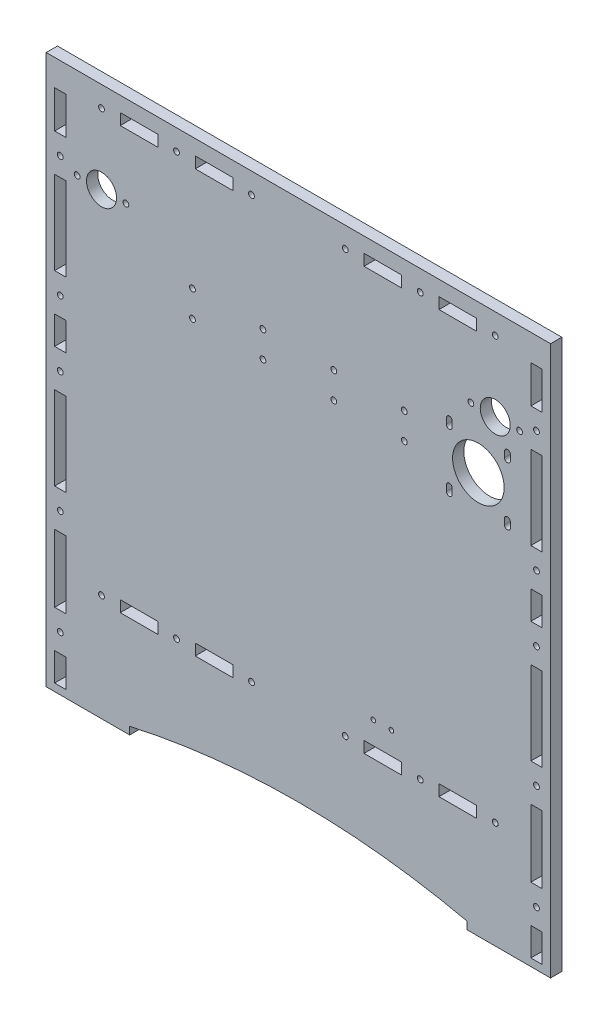
SolidWorks part; units mm, degrees
ref_plane "Front Plane" through (0, 0, 0) normal (0, 0, 1) x (1, 0, 0)
ref_plane "Top Plane" through (0, 0, 0) normal (0, 1, 0) x (1, 0, 0)
ref_plane "Right Plane" through (0, 0, 0) normal (1, 0, 0) x (0, 0, -1)
sketch "Sketch1" plane through (0, 0, 0) normal (0, 0, 1) x (1, 0, 0)
  line L1 (0, 0) -> (260, 0)
  line L2 (0, 0) -> (0, 270)
  line L3 (0, 270) -> (260, 270)
  line L4 (260, 0) -> (260, 270)
  dimension "D1" = 270
  dimension "D2" = 260
extrude "Boss-Extrude1" add sketch "Sketch1" along normal blind 6
sketch "Sketch2" plane through (0, 0, 0) normal (0, 0, -1) x (-1, 0, 0)
  line L0 (-130, 270) -> (-130, 0) construction
  line L1 (-225, 56) -> (-205, 56)
  line L2 (-225, 56) -> (-225, 50)
  line L3 (-225, 50) -> (-205, 50)
  line L4 (-205, 56) -> (-205, 50)
  line L5 (-185, 56) -> (-165, 56)
  line L6 (-185, 56) -> (-185, 50)
  line L7 (-185, 50) -> (-165, 50)
  line L8 (-165, 56) -> (-165, 50)
  line L9 (-260, 270) -> (0, 270) construction
  line L10 (0, 0) -> (-260, 0) construction
  line L11 (-260, 0) -> (-260, 270) construction
  line L12 (-225, 53) -> (-165, 53) construction
  line L13 (-130, 0) -> (-130, -73.8705) construction
  line L14 (-130, -73.8705) -> (-130, -196.098) construction
  line L16 (-220, 0) -> (-40, 0)
  line L17 (-75, 50) -> (-95, 50)
  line L18 (-95, 56) -> (-95, 50)
  line L19 (-75, 56) -> (-95, 56)
  line L20 (-75, 56) -> (-75, 50)
  line L21 (-35, 50) -> (-55, 50)
  line L22 (-55, 56) -> (-55, 50)
  line L23 (-35, 56) -> (-55, 56)
  line L24 (-35, 56) -> (-35, 50)
  arc A0 (-220, 0) -> (-40, 0) centre (-130, -400) cw
  point P23 (-130, 10)
  point P26 (-130, 10)
  dimension "D9" = 40
  dimension "D1" = 35
  dimension "D2" = 20
  dimension "D3" = 20
  dimension "D4" = 20
  dimension "D5" = 6
  dimension "D6" = 6
  dimension "D7" = 50
  dimension "D8" = 3
  dimension "D12" = 10
extrude "Cut-Extrude1" cut sketch "Sketch2" against normal blind 6
sketch "Sketch4" plane through (0, 0, 0) normal (0, 0, -1) x (-1, 0, 0)
  line L1 (-260, 270) -> (-254, 270)
  line L2 (-260, 270) -> (-260, 264)
  line L5 (-220, 0) -> (-260, 0) construction
  line L6 (-260, 270) -> (-254, 270)
  line L7 (-260, 270) -> (-260, 255)
  line L8 (-260, 0) -> (-254, 0)
  line L9 (-254, 264) -> (-254, 255)
  line L11 (-254, 15) -> (-260, 15)
  line L13 (-254, 35) -> (-260, 35)
  line L15 (-254, 71) -> (-260, 71)
  line L17 (-254, 91) -> (-260, 91)
  line L19 (-260, 135.5) -> (-254, 135.5)
  line L21 (-260, 155.5) -> (-254, 155.5)
  line L23 (-254, 170.5) -> (-260, 170.5)
  line L25 (-254, 190.5) -> (-260, 190.5)
  line L27 (-254, 235) -> (-260, 235)
  line L29 (-254, 255) -> (-260, 255)
  line L33 (-254, 264) -> (-254, 270)
  line L36 (-205, 56) -> (-225, 56) construction
  line L38 (-130, 270) -> (-130, 0) construction
  line L39 (-260, 270) -> (0, 270) construction
  line L40 (-260, 15) -> (-260, 0)
  line L41 (-260, 270) -> (-254, 270)
  line L42 (-260, 270) -> (-260, 255)
  line L43 (-260, 255) -> (-254, 255)
  line L44 (-254, 270) -> (-254, 255)
  line L45 (-260, 235) -> (-254, 235)
  line L46 (-260, 235) -> (-260, 190.5)
  line L47 (-260, 190.5) -> (-254, 190.5)
  line L48 (-254, 235) -> (-254, 190.5)
  line L49 (-260, 170.5) -> (-254, 170.5)
  line L50 (-260, 170.5) -> (-260, 155.5)
  line L51 (-260, 155.5) -> (-254, 155.5)
  line L52 (-254, 170.5) -> (-254, 155.5)
  line L53 (-260, 135.5) -> (-254, 135.5)
  line L54 (-260, 135.5) -> (-260, 91)
  line L55 (-260, 91) -> (-254, 91)
  line L56 (-254, 135.5) -> (-254, 91)
  line L57 (-260, 71) -> (-254, 71)
  line L58 (-260, 71) -> (-260, 35)
  line L59 (-260, 35) -> (-254, 35)
  line L60 (-254, 71) -> (-254, 35)
  line L61 (-260, 15) -> (-254, 15)
  line L62 (-260, 15) -> (-260, 0)
  line L63 (-260, 0) -> (-254, 0)
  line L64 (-254, 15) -> (-254, 0)
  line L65 (-254, 71) -> (-254, 35)
  line L66 (-260, 71) -> (-260, 35)
  line L67 (-254, 135.5) -> (-254, 91)
  line L68 (-260, 135.5) -> (-260, 91)
  line L69 (-254, 170.5) -> (-254, 155.5)
  line L70 (-260, 170.5) -> (-260, 155.5)
  line L71 (-254, 235) -> (-254, 190.5)
  line L72 (-260, 235) -> (-260, 190.5)
  line L73 (-254, 15) -> (-254, 0)
  line L74 (0, 0) -> (-6, 0)
  line L75 (-6, 15) -> (-6, 0)
  line L76 (0, 15) -> (-6, 15)
  line L77 (0, 15) -> (0, 0)
  line L78 (0, 35) -> (-6, 35)
  line L79 (-6, 71) -> (-6, 35)
  line L80 (0, 71) -> (-6, 71)
  line L81 (0, 71) -> (0, 35)
  line L82 (0, 91) -> (-6, 91)
  line L83 (-6, 135.5) -> (-6, 91)
  line L84 (0, 135.5) -> (-6, 135.5)
  line L85 (0, 135.5) -> (0, 91)
  line L86 (0, 155.5) -> (-6, 155.5)
  line L87 (-6, 170.5) -> (-6, 155.5)
  line L88 (0, 170.5) -> (-6, 170.5)
  line L89 (0, 170.5) -> (0, 155.5)
  line L90 (0, 190.5) -> (-6, 190.5)
  line L91 (-6, 235) -> (-6, 190.5)
  line L92 (0, 235) -> (-6, 235)
  line L93 (0, 235) -> (0, 190.5)
  line L94 (0, 255) -> (-6, 255)
  line L95 (-6, 270) -> (-6, 255)
  line L96 (0, 270) -> (-6, 270)
  line L97 (0, 270) -> (0, 255)
  point P33 (-257, 170.5)
  point P34 (-257, 71)
  line M60 (-40, 0) -> (0, 0)
  line M61 (0, 0) -> (0, 270)
  line M62 (0, 270) -> (-260, 270)
  line M63 (-260, 270) -> (-260, 0)
  line M64 (-260, 0) -> (-220, 0)
  dimension "D1" = 6
  dimension "D2" = 15
  dimension "D3" = 20
  dimension "D4" = 20
  dimension "D5" = 15
  dimension "D6" = 44.5
  dimension "D7" = 15
  dimension "D8" = 20
  dimension "D10" = 20
  dimension "D11" = 20
  dimension "D12" = 15
extrude "Cut-Extrude3" cut sketch "Sketch4" against normal blind 6 contours L9 L33 L29 M62 M63 | L48 L27 L25 M63 | L52 L23 L21 M63 | L56 L19 L17 M63 | L60 L15 L13 M63 | L64 L11 M63 M64 | L76 L75 M61 M60 | L80 L79 L78 M61 | L84 L83 L82 M61 | L92 L91 L90 M61 | L95 L94 M62 M61 | L89 L86 L87 L88
sketch "Sketch5" plane through (0, 0, 0) normal (0, 0, -1) x (-1, 0, 0)
  line L0 (-130, 270) -> (-130, 190.9639) construction
  line L1 (-254, 270) -> (-6, 270) construction
  line L2 (-260, 235) -> (-260, 255) construction
  circle A0 centre (-235, 240.5) radius 8
  circle A1 centre (-25, 240.5) radius 8
  dimension "D1" = 16
  dimension "D3" = 25
  dimension "D2" = 29.5
extrude "Cut-Extrude4" cut sketch "Sketch5" against normal blind 10
sketch "Sketch6" plane through (0, 0, 0) normal (0, 0, -1) x (-1, 0, 0)
  line L0 (-130, 270) -> (-130, 162.347) construction
  line L1 (-254, 270) -> (-6, 270) construction
  line L2 (-243, 240.5) -> (-227, 240.5) construction
  line L3 (-235, 248.5) -> (-235, 232.5) construction
  line L4 (-248, 240.5) -> (-222, 240.5) construction
  line L5 (-254, 235) -> (-254, 190.5) construction
  circle A0 centre (-235, 240.5) radius 8 construction
  circle A1 centre (-235, 240.5) radius 8
  circle A2 centre (-248, 240.5) radius 1.55
  circle A3 centre (-222, 240.5) radius 1.55
  circle A4 centre (-12, 240.5) radius 1.55
  circle A5 centre (-38, 240.5) radius 1.55
  dimension "D4" = 3.1
  dimension "D3" = 6
extrude "Cut-Extrude5" cut sketch "Sketch6" against normal blind 6
sketch "Sketch7" plane through (0, 0, 0) normal (0, 0, -1) x (-1, 0, 0)
  line L0 (-130, 270) -> (-130, 302.4373) construction
  line L1 (-254, 270) -> (-6, 270) construction
  line L2 (-186.5, 219) -> (-186.5, 205) construction
  line L4 (-189.7779, 212) -> (-134.7801, 212) construction
  circle A0 centre (-186.5, 205) radius 1.55
  circle A1 centre (-148.9, 205) radius 1.55
  circle A2 centre (-148.9, 219) radius 1.55
  circle A3 centre (-186.5, 219) radius 1.55
  circle A4 centre (-73.5, 205) radius 1.55
  circle A5 centre (-111.1, 205) radius 1.55
  circle A6 centre (-111.1, 219) radius 1.55
  circle A7 centre (-73.5, 219) radius 1.55
  dimension "D1" = 3.1
  dimension "D4" = 7
  dimension "D5" = 37.6
  dimension "D6" = 14
  dimension "D7" = 56.5
  dimension "D8" = 58
  dimension "D2" = 2
  dimension "D3" = 2
extrude "Cut-Extrude6" cut sketch "Sketch7" against normal blind 10
sketch "Sketch8" plane through (0, 270, 0) normal (0, 1, 0) x (1, 0, 0)
  line L4 (254, 0) -> (6, 0)
  line L5 (6, 0) -> (6, -6)
  line L6 (6, -6) -> (254, -6)
  line L7 (254, -6) -> (254, 0)
  line L8 (254, 0) -> (6, 0)
  line L9 (6, 0) -> (6, -6)
  line L10 (6, -6) -> (254, -6)
  line L11 (254, -6) -> (254, 0)
  dimension "D1" = 0
extrude "Boss-Extrude2" add sketch "Sketch8" along normal blind 5
sketch "Sketch9" plane through (0, 0, 0) normal (0, 0, -1) x (-1, 0, 0)
  line L1 (0, 0) -> (4.5, 0)
  line L2 (0, 0) -> (0, 275)
  line L4 (4.5, 0) -> (4.5, 275)
  line L5 (4.5, 275) -> (0, 275)
  line L6 (-260, 275) -> (-264.5, 275)
  line L11 (-260, 0) -> (-264.5, 0)
  line L12 (-260, 0) -> (-260, 275)
  line L14 (-264.5, 0) -> (-264.5, 275)
  line L15 (-260, 235) -> (-260, 255) construction
  dimension "D1" = 275
  dimension "D2" = 4.5
  dimension "D4" = 0
  dimension "D5" = 4.5
extrude "Boss-Extrude5" add sketch "Sketch9" against normal blind 6
sketch "Sketch10" plane through (0, 0, 6) normal (0, 0, 1) x (1, 0, 0)
  line L0 (226, 173.146) -> (226, 224.7535) construction
  line L1 (176.5903, 210.0523) -> (229.2937, 210.0523) construction
  line L2 (241.5, 194.5523) -> (210.5, 194.5523) construction
  line L3 (241.5, 194.5523) -> (241.5, 225.5523) construction
  line L4 (241.5, 225.5523) -> (210.5, 225.5523) construction
  line L5 (210.5, 194.5523) -> (210.5, 225.5523) construction
  line L6 (241.5, 194.5523) -> (210.5, 225.5523) construction
  line L7 (241.5, 225.5523) -> (210.5, 194.5523) construction
  line L8 (264.5, 275) -> (264.5, 0) construction
  line L10 (210.5, 224.0523) -> (210.5, 227.0523) construction
  line L11 (208.95, 224.0523) -> (208.95, 227.0523)
  line L12 (212.05, 224.0523) -> (212.05, 227.0523)
  line L13 (243.05, 224.0523) -> (243.05, 227.0523)
  line L14 (239.95, 224.0523) -> (239.95, 227.0523)
  line L15 (241.5, 224.0523) -> (241.5, 227.0523) construction
  line L16 (243.05, 193.0523) -> (243.05, 196.0523)
  line L17 (239.95, 193.0523) -> (239.95, 196.0523)
  line L18 (241.5, 193.0523) -> (241.5, 196.0523) construction
  line L19 (212.05, 193.0523) -> (212.05, 196.0523)
  line L20 (208.95, 193.0523) -> (208.95, 196.0523)
  line L21 (210.5, 193.0523) -> (210.5, 196.0523) construction
  circle A0 centre (226, 210.0523) radius 13.75
  arc A6 (208.95, 224.0523) -> (212.05, 224.0523) centre (210.5, 224.0523) ccw
  arc A7 (212.05, 227.0523) -> (208.95, 227.0523) centre (210.5, 227.0523) ccw
  arc A8 (239.95, 224.0523) -> (243.05, 224.0523) centre (241.5, 224.0523) ccw
  arc A9 (243.05, 227.0523) -> (239.95, 227.0523) centre (241.5, 227.0523) ccw
  arc A10 (239.95, 193.0523) -> (243.05, 193.0523) centre (241.5, 193.0523) ccw
  arc A11 (243.05, 196.0523) -> (239.95, 196.0523) centre (241.5, 196.0523) ccw
  arc A12 (208.95, 193.0523) -> (212.05, 193.0523) centre (210.5, 193.0523) ccw
  arc A13 (212.05, 196.0523) -> (208.95, 196.0523) centre (210.5, 196.0523) ccw
  circle A14 centre (235, 240.5) radius 8 construction
  circle A15 centre (235, 240.5) radius 8 construction
  point P12 (241.5, 225.5523)
  point P23 (210.5, 225.5523)
  point P32 (241.5, 194.5523)
  point P39 (210.5, 194.5523)
  dimension "D1" = 27.5
  dimension "D2" = 3.1
  dimension "D3" = 3
  dimension "D6" = 2
  dimension "D9" = 2
  dimension "D10" = 15.5
  dimension "D5" = 15.5
  dimension "D7" = 23
  dimension "D8" = 31.75
  dimension "D4" = 15.5
extrude "Cut-Extrude7" cut sketch "Sketch10" against normal blind 6
sketch "Sketch11" plane through (0, 0, 6) normal (0, 0, 1) x (1, 0, 0)
  line L0 (130, 275) -> (130, 250) construction
  line L1 (6, 275) -> (254, 275) construction
  line L2 (3, 275) -> (3, -100) construction
  line L3 (6, 235) -> (6, 190.5) construction
  line L4 (0, 235) -> (6, 235) construction
  line L5 (0, 190.5) -> (6, 190.5) construction
  line L6 (0, 155.5) -> (6, 155.5) construction
  line L7 (0, 91) -> (6, 91) construction
  line L8 (0, 35) -> (6, 35) construction
  circle A0 centre (3, 245) radius 1.55
  circle A1 centre (3, 180.5) radius 1.55
  circle A2 centre (3, 145.5) radius 1.55
  circle A3 centre (3, 81) radius 1.55
  circle A4 centre (3, 25) radius 1.55
  circle A5 centre (257, 25) radius 1.55
  circle A6 centre (257, 81) radius 1.55
  circle A7 centre (257, 145.5) radius 1.55
  circle A8 centre (257, 180.5) radius 1.55
  circle A9 centre (257, 245) radius 1.55
  dimension "D2" = 10
  dimension "D3" = 3.1
  dimension "D4" = 3.1
  dimension "D5" = 10
  dimension "D6" = 3.1
  dimension "D7" = 10
  dimension "D8" = 3.1
  dimension "D9" = 10
  dimension "D10" = 10
  dimension "D11" = 3.1
  dimension "D1" = 3
extrude "Cut-Extrude8" cut sketch "Sketch11" against normal blind 6
sketch "Sketch12" plane through (0, 0, 6) normal (0, 0, 1) x (1, 0, 0)
  line L0 (-4.5, 53) -> (264.5, 53) construction
  line L1 (-4.5, 0) -> (-4.5, 275) construction
  line L2 (264.5, 275) -> (264.5, 0) construction
  line L3 (130, 53) -> (130, 40.9618) construction
  line L4 (75, 50) -> (75, 56) construction
  line L5 (6, 0) -> (40, 0) construction
  line L6 (95, 56) -> (95, 50) construction
  line L7 (35, 50) -> (35, 56) construction
  circle A0 centre (25, 53) radius 1.55
  circle A1 centre (65, 53) radius 1.55
  circle A2 centre (105, 53) radius 1.55
  circle A3 centre (155, 53) radius 1.55
  circle A4 centre (195, 53) radius 1.55
  circle A5 centre (235, 53) radius 1.55
  dimension "D1" = 3.1
  dimension "D2" = 3.1
  dimension "D3" = 3.1
  dimension "D4" = 10
  dimension "D5" = 10
  dimension "D6" = 10
  dimension "D7" = 53
extrude "Cut-Extrude9" cut sketch "Sketch12" against normal blind 10
sketch "Sketch13" plane through (0, 0, 0) normal (0, -1, 0) x (1, 0, 0)
  line L1 (-4.5, 6) -> (40, 6)
  line L2 (-4.5, 6) -> (-4.5, 0)
  line L3 (-4.5, 0) -> (40, 0)
  line L4 (40, 6) -> (40, 0)
  line L5 (220, 6) -> (264.5, 6)
  line L6 (220, 6) -> (220, 0)
  line L7 (220, 0) -> (264.5, 0)
  line L8 (264.5, 6) -> (264.5, 0)
extrude "Boss-Extrude6" add sketch "Sketch13" along normal blind 4
sketch "Sketch14" plane through (0, 275, 0) normal (0, 1, 0) x (1, 0, 0)
  line L1 (-4.5, -6) -> (264.5, -6)
  line L2 (-4.5, -6) -> (-4.5, 0)
  line L3 (-4.5, 0) -> (264.5, 0)
  line L4 (264.5, -6) -> (264.5, 0)
extrude "Boss-Extrude7" add sketch "Sketch14" along normal blind 14
sketch "Sketch15" plane through (0, 0, 6) normal (0, 0, 1) x (1, 0, 0)
  line L32 (35, 281) -> (55, 281)
  line L33 (55, 281) -> (55, 275)
  line L34 (55, 275) -> (35, 275)
  line L35 (35, 275) -> (35, 281)
  line L36 (75, 281) -> (95, 281)
  line L37 (95, 281) -> (95, 275)
  line L38 (95, 275) -> (75, 275)
  line L39 (75, 275) -> (75, 281)
  line L40 (165, 281) -> (185, 281)
  line L41 (185, 281) -> (185, 275)
  line L42 (185, 275) -> (165, 275)
  line L43 (165, 275) -> (165, 281)
  line L44 (205, 281) -> (225, 281)
  line L45 (225, 281) -> (225, 275)
  line L46 (225, 275) -> (205, 275)
  line L47 (205, 275) -> (205, 281)
  line L48 (130, 289) -> (130, 318.7386) construction
  line L49 (-4.5, 289) -> (264.5, 289) construction
  circle A12 centre (25, 278) radius 1.55
  circle A13 centre (65, 278) radius 1.55
  circle A14 centre (105, 278) radius 1.55
  circle A15 centre (155, 278) radius 1.55
  circle A16 centre (195, 278) radius 1.55
  circle A17 centre (235, 278) radius 1.55
  point P4 (225, 278)
  dimension "D1" = 11
  dimension "D2" = 11
  dimension "D3" = 11
  dimension "D4" = 25
  dimension "D5" = 40
  dimension "D6" = 40
  dimension "D7" = 10
  dimension "D8" = 10
extrude "Cut-Extrude10" cut sketch "Sketch15" against normal blind 10
sketch "Sketch16" plane through (0, 0, 6) normal (0, 0, 1) x (1, 0, 0)
  line L0 (-33.5909, 68) -> (347.9098, 68) construction
  line L1 (35, 56) -> (55, 56) construction
  line L2 (130, 289) -> (130, -4.5233) construction
  line L3 (-4.5, 289) -> (264.5, 289) construction
  circle A0 centre (179.6, 68) radius 1.25
  circle A1 centre (170, 68) radius 1.25
  dimension "D2" = 2.5
  dimension "D3" = 2.5
  dimension "D4" = 9.6
  dimension "D5" = 40
  dimension "D1" = 12
extrude "Cut-Extrude11" cut sketch "Sketch16" against normal blind 10
